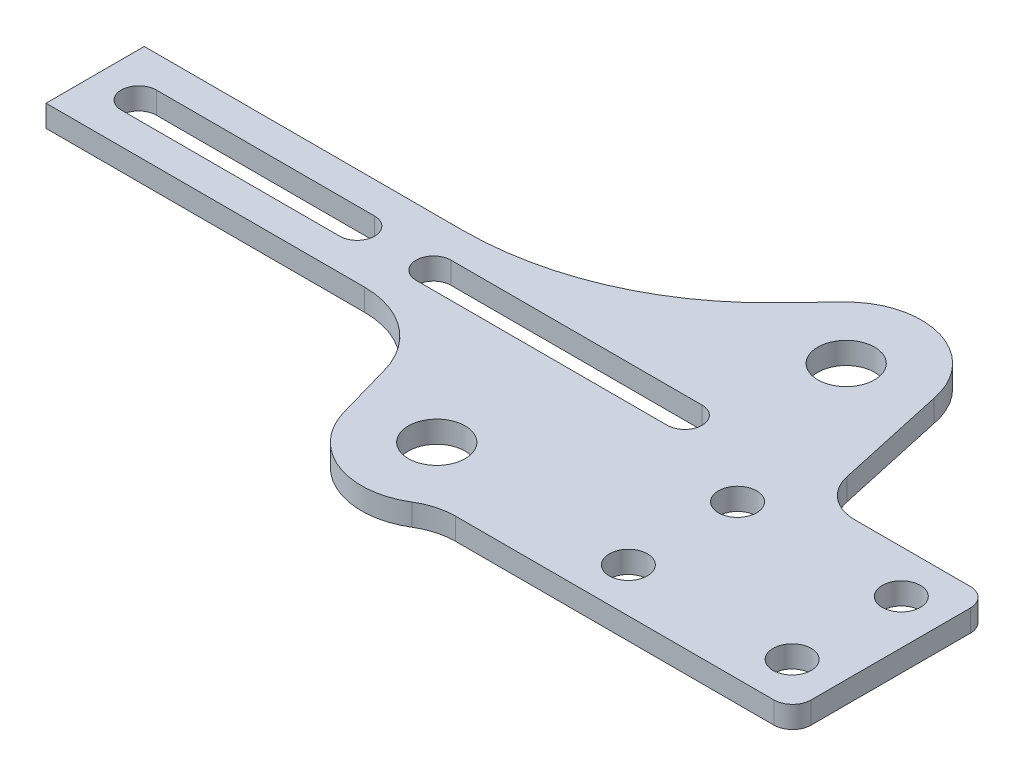
SolidWorks part; units mm, degrees
ref_plane "前视基准面" through (0, 0, 0) normal (0, 0, 1) x (1, 0, 0)
ref_plane "上视基准面" through (0, 0, 0) normal (0, 1, 0) x (1, 0, 0)
ref_plane "右视基准面" through (0, 0, 0) normal (1, 0, 0) x (0, 0, -1)
other "Configuration Table"
sketch "草图2" plane through (0, 0, 0) normal (0, 1, 0) x (1, 0, 0)
  line L4 (-1.25, 14) -> (15, 14)
  line L5 (15, 14) -> (15, -3.9965) construction
  line L6 (15, -3.9965) -> (-13.75, -3.9965)
  line L15 (-10.75, 31.0035) -> (-1.25, 31.0035)
  line L16 (-1.25, 31.0035) -> (-1.25, 14)
  line L18 (-13.75, -3.9965) -> (-23.25, -3.9965)
  line L19 (-23.25, -3.9965) -> (-23.25, 10.0035)
  line L20 (-23.25, 10.0035) -> (-37.2935, 10.0035)
  line L21 (-37.2935, 10.0035) -> (-37.2935, 19.0035)
  line L22 (-37.2935, 19.0035) -> (-10.75, 19.0035)
  line L23 (-10.75, 19.0035) -> (-10.75, 31.0035)
  line L24 (15, 14) -> (17.3739, 14)
  line L25 (17.3739, 14) -> (17.3739, -3.9965)
  line L26 (7.5, -25.2685) -> (15, -25.2685)
  line L27 (15, -25.2685) -> (15, -45.5251)
  line L28 (15, -45.5251) -> (-27, -45.5251)
  line L29 (-6, -71.3903) -> (-6, 35.8058) construction
  line L30 (-12.25, -49.7584) -> (-12.25, 37.3591) construction
  line L31 (0.25, -49.7584) -> (0.25, 37.3591) construction
  line L32 (-18.5, -30.3985) -> (-18.5, 21.2262) construction
  line L33 (17.3739, -3.9965) -> (15, -3.9965)
  circle A4 centre (-6, 26.0035) radius 2.6
  circle A5 centre (-18.5, 1.0035) radius 2.6
  circle A6 centre (15, 10.0532) radius 1.75
  circle A7 centre (0, 10.0532) radius 1.75
  circle A8 centre (0, 0.0532) radius 1.75
  circle A9 centre (15, 0.0532) radius 1.75
  dimension "D3" = 2
  dimension "D10" = 5.2
  dimension "D11" = 5.2
  dimension "D2" = 3.5
  dimension "D7" = 42
  dimension "D8" = 21
  dimension "D9" = 12.5
  dimension "D12" = 6.25
  dimension "D14" = 9
  dimension "D15" = 7
  dimension "D16" = 9
  dimension "D17" = 12
  dimension "D18" = 14
  dimension "D5" = 1.5
  dimension "D4" = 2
extrude "凸台-拉伸3" add sketch "草图2" along normal blind 2
sketch "草图3" plane through (0, 2, 0) normal (0, 1, 0) x (1, 0, 0)
  line L0 (-23.25, 10.0035) -> (-37.2935, 10.0035) construction
  line L1 (-25.1335, -0.883) -> (-26.6243, 4.3589)
  line L2 (-34.098, 10.0035) -> (-23.25, 10.0035)
  line L3 (-23.25, 10.0035) -> (-23.25, 6.0035)
  line L4 (-23.25, -3.9965) -> (-23.25, 10.0035) construction
  line L5 (-10.955, 30.8005) -> (-14.1966, 27.4521)
  line L6 (-37.2935, 19.0035) -> (-10.75, 19.0035) construction
  line L7 (-34.1349, 19.0035) -> (-6, 19.0035)
  line L8 (-6, 19.0035) -> (-6, 19.107)
  line L9 (-23.25, 10.0035) -> (-23.25, 6.0035)
  circle A0 centre (-18.5, 1.0035) radius 6.8966
  arc A1 (-26.6243, 4.3589) -> (-34.098, 10.0035) centre (-34.098, 2.2335) ccw
  circle A2 centre (-6, 26.0035) radius 6.8966
  arc A3 (-14.1966, 27.4521) -> (-34.1349, 19.0035) centre (-34.1349, 46.7546) cw
  circle A4 centre (-18.5, 1.0035) radius 2.6 construction
  circle A5 centre (-6, 26.0035) radius 2.6 construction
  circle A6 centre (-18.5, 1.0035) radius 2.6
  circle A7 centre (-6, 26.0035) radius 2.6
  circle M12 centre (-18.5, 1.0035) radius 2.6
  circle M13 centre (-6, 26.0035) radius 2.6
  line M14 (-23.25, -3.9965) -> (17.3739, -3.9965)
  line M17 (-1.25, 14) -> (-1.25, 31.0035)
  line M18 (-1.25, 31.0035) -> (-10.75, 31.0035)
  line M19 (-10.75, 31.0035) -> (-10.75, 19.0035)
  line M20 (-10.75, 19.0035) -> (-37.2935, 19.0035)
  line M22 (-37.2935, 10.0035) -> (-23.25, 10.0035)
  line M23 (-23.25, 10.0035) -> (-23.25, -3.9965)
extrude "凸台-拉伸4" add sketch "草图3" against normal blind 2 contours A2 M17 M18 M19 M13 | L5 A3 A2 M20 M19 | A2 M18 | A2 M17 | A1 L1 A0 M23 M22 | A0 M14 M23 M12 | A0 M23 | A0 M14 | A2 M19
sketch "草图4" plane through (0, 0, 0) normal (0, -1, 0) x (1, 0, 0)
  line L0 (0.6881, -27.6865) -> (3.0237, -17.0336)
  line L1 (-1.25, -14) -> (17.3739, -14) construction
  line L2 (-1.25, -21.0035) -> (-1.25, -14) construction
  line L3 (-1.25, -14) -> (6.7944, -14)
  line L4 (-1.25, -21.0035) -> (-1.25, -14)
  arc A0 (-10.955, -30.8005) -> (-1.25, -21.0035) centre (-6, -26.0035) ccw construction
  arc A1 (3.0237, -17.0336) -> (6.7944, -14) centre (6.7944, -17.8603) cw
  arc A2 (0.6881, -27.6865) -> (-1.25, -21.0035) centre (-6, -26.0035) ccw
  arc M4 (-10.955, -30.8005) -> (-1.25, -21.0035) centre (-6, -26.0035) ccw
  line M5 (-1.25, -21.0035) -> (-1.25, -14)
  line M6 (-1.25, -14) -> (17.3739, -14)
extrude "凸台-拉伸5" add sketch "草图4" against normal blind 2 contours L0 A1 M6 M5 M4
fillet "圆角1" radius 6 1 edges at (-13.75, 1, 3.9965)
sketch "草图6" plane through (0, 2, 0) normal (0, 1, 0) x (1, 0, 0)
  line L0 (17.3739, 14) -> (-2.6261, 14)
  line L1 (-2.6261, 14) -> (-2.6261, -10.4586) construction
  line L2 (-45.1185, 14.5035) -> (-9.6558, 14.5035) construction
  line L4 (-37.2935, 19.0035) -> (-34.1349, 19.0035) construction
  line L5 (-34.098, 10.0035) -> (-37.2935, 10.0035) construction
  line L6 (-32.2935, 14.5035) -> (-9.2935, 14.5035) construction
  line L7 (-32.2935, 16.1035) -> (-9.2935, 16.1035)
  line L8 (-32.2935, 12.9035) -> (-9.2935, 12.9035)
  line L9 (-37.2935, 10.0035) -> (-37.2935, 19.0035) construction
  arc A0 (-32.2935, 16.1035) -> (-32.2935, 12.9035) centre (-32.2935, 14.5035) ccw
  arc A1 (-9.2935, 12.9035) -> (-9.2935, 16.1035) centre (-9.2935, 14.5035) ccw
  point P14 (-20.7935, 14.5035)
  dimension "D2" = 1.6
  dimension "D1" = 20
  dimension "D3" = 23
  dimension "D4" = 5
extrude "切除-拉伸1" cut sketch "草图6" against normal blind 2 contours L8 A1 L7 A0
sketch "草图7" plane through (0, 2, 0) normal (0, 1, 0) x (1, 0, 0)
  line L0 (19.0853, 12.2887) -> (19.0853, -2.2851)
  line L1 (11.9935, 5.0018) -> (27.9101, 5.0018) construction
  line L2 (6.7944, 14) -> (17.3739, 14) construction
  line L3 (17.3739, -3.9965) -> (-11.7679, -3.9965) construction
  line L4 (17.3739, 14) -> (17.3739, -3.9965)
  arc A0 (19.0853, -2.2851) -> (17.3739, -3.9965) centre (17.3739, -2.2851) cw
  arc A1 (19.0853, 12.2887) -> (17.3739, 14) centre (17.3739, 12.2887) ccw
  point P16 (19.0853, 5.0018)
extrude "凸台-拉伸6" add sketch "草图7" against normal blind 2
sketch "草图8" plane through (0, 2, 0) normal (0, 1, 0) x (1, 0, 0)
  line L0 (-37.2935, 10.0035) -> (-63.2935, 10.0035)
  line L1 (-63.2935, 10.0035) -> (-63.2935, 19.0035)
  line L2 (-63.2935, 19.0035) -> (-37.2935, 19.0035)
  line L3 (-59.2935, 14.5035) -> (-39.2935, 14.5035) construction
  line L4 (-59.2935, 16.1035) -> (-39.2935, 16.1035)
  line L5 (-59.2935, 12.9035) -> (-39.2935, 12.9035)
  line L6 (-32.2935, 16.1035) -> (-9.2935, 16.1035) construction
  line L7 (-32.2935, 12.9035) -> (-9.2935, 12.9035) construction
  arc A0 (-59.2935, 16.1035) -> (-59.2935, 12.9035) centre (-59.2935, 14.5035) ccw
  arc A1 (-39.2935, 12.9035) -> (-39.2935, 16.1035) centre (-39.2935, 14.5035) ccw
  point P8 (-49.2935, 14.5035)
  line M20 (-37.2935, 19.0035) -> (-37.2935, 10.0035)
  dimension "D2" = 20
  dimension "D1" = 26
  dimension "D3" = 4
extrude "凸台-拉伸7" add sketch "草图8" against normal blind 2 contours L2 L1 L0 A1 L5 A0 L4 M20
